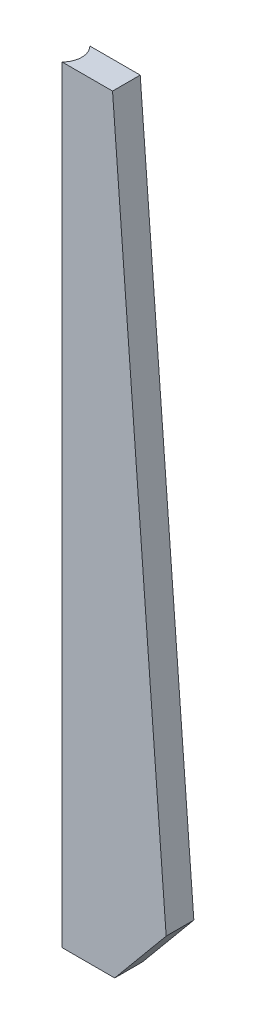
SolidWorks part; units mm, degrees
ref_plane "Front Plane" through (0, 0, 0) normal (0, 0, 1) x (1, 0, 0)
ref_plane "Top Plane" through (0, 0, 0) normal (0, 1, 0) x (1, 0, 0)
ref_plane "Right Plane" through (0, 0, 0) normal (1, 0, 0) x (0, 0, -1)
sketch "Sketch3" plane through (0, 0, 0) normal (0, 0, 1) x (1, 0, 0)
  line L2 (373.3741, 416.9681) -> (402.4374, 34.9102)
  line L4 (346.0749, 1.2981) -> (374.5398, 1.2981)
  line L6 (346.0749, 180.3339) -> (391.3749, 180.3339) construction
  line L8 (346.0749, 1.2981) -> (346.0749, 416.9681)
  line L9 (346.0749, 416.9681) -> (373.3741, 416.9681)
  line L13 (402.4374, 34.9102) -> (374.5398, 1.2981)
  point P0 (368.7249, 180.3339)
  point P2 (391.3749, 180.3339)
  point P8 (0, 0)
  point P9 (0, 0)
  point P10 (359.7245, 416.9681)
  point P12 (399.7877, 33.0086)
  point P13 (391.3749, 72.1347)
  point P14 (402.4374, 34.9102)
  dimension "D1" = 45.3
  dimension "D2" = 415.67
extrude "Boss-Extrude1" add sketch "Sketch3" along normal blind 15
scale "Scale1" scale about centroid uniform scaling yes scale factor 0.6
ref_plane "Plane2" through (0, 184.5, 0) normal (0, 1, 0) x (1, 0, 0)
sketch "Sketch9" plane through (0, 184.5, 0) normal (0, 1, 0) x (1, 0, 0)
  line L0 (354.7847, -12) -> (354.7847, -3)
  arc A0 (354.7847, -12) -> (354.7847, -3) centre (350.2847, -7.5) ccw
extrude "Cut-Extrude2" cut sketch "Sketch9" against normal through all both and the other way through all
